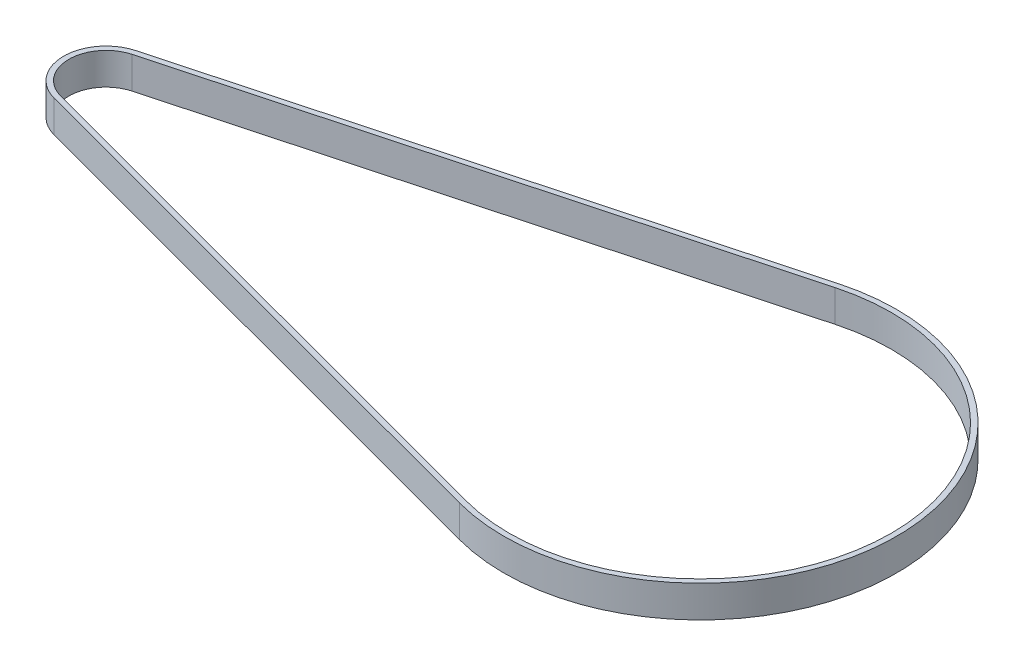
SolidWorks part; units mm, degrees
ref_plane "Front Plane" through (0, 0, 0) normal (0, 0, 1) x (1, 0, 0)
ref_plane "Top Plane" through (0, 0, 0) normal (0, 1, 0) x (1, 0, 0)
ref_plane "Right Plane" through (0, 0, 0) normal (1, 0, 0) x (0, 0, -1)
sketch "Sketch1" plane through (0, 0, 0) normal (0, 1, 0) x (1, 0, 0)
  line L0 (-1.5251, -7.668) -> (102.7467, -35.5347)
  line L1 (-1.5459, 7.784) -> (102.6507, 35.9305)
  line L2 (-1.267, -6.7019) -> (103.0048, -34.5686)
  line L3 (-1.2851, 6.8186) -> (102.9115, 34.9651)
  circle A2 centre (0.5404, 0.0608) radius 8 construction
  arc A3 (-1.5459, 7.784) -> (-1.5251, -7.668) centre (0.5404, 0.0608) ccw
  circle A4 centre (112.2997, 0.2108) radius 37 construction
  arc A5 (102.7467, -35.5347) -> (102.6507, 35.9305) centre (112.2997, 0.2108) ccw
  arc A6 (103.0048, -34.5686) -> (102.9115, 34.9651) centre (112.2997, 0.2108) ccw
  arc A7 (-1.2851, 6.8186) -> (-1.267, -6.7019) centre (0.5404, 0.0608) ccw
  point P1 (0, 0)
  point P3 (0, 0)
  dimension "D1" = 1
extrude "Boss-Extrude1" add sketch "Sketch1" along normal blind 6
